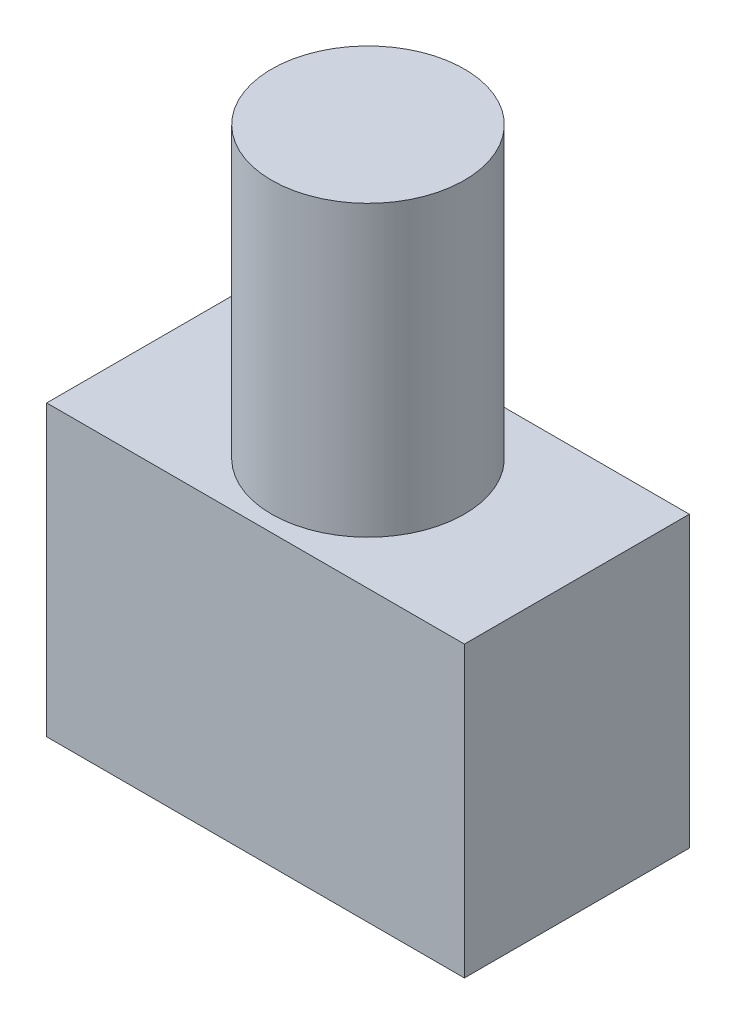
SolidWorks part; units mm, degrees
ref_plane "Front Plane" through (0, 0, 0) normal (0, 0, 1) x (1, 0, 0)
ref_plane "Top Plane" through (0, 0, 0) normal (0, 1, 0) x (1, 0, 0)
ref_plane "Right Plane" through (0, 0, 0) normal (1, 0, 0) x (0, 0, -1)
sketch "Sketch1" plane through (0, 0, 0) normal (0, 1, 0) x (1, 0, 0)
  line L1 (-6.5, 3.5) -> (6.5, 3.5)
  line L2 (-6.5, 3.5) -> (-6.5, -3.5)
  line L3 (-6.5, -3.5) -> (6.5, -3.5)
  line L4 (6.5, 3.5) -> (6.5, -3.5)
  line L5 (-6.5, 3.5) -> (6.5, -3.5) construction
  line L6 (-6.5, -3.5) -> (6.5, 3.5) construction
  point P0 (0, 0)
  dimension "D1" = 7
  dimension "D2" = 13
extrude "Boss-Extrude1" add sketch "Sketch1" along normal blind 9
sketch "Sketch2" plane through (0, 9, 0) normal (0, 1, 0) x (1, 0, 0)
  circle A0 centre (0, 0) radius 3
  dimension "D1" = 6
extrude "Boss-Extrude2" add sketch "Sketch2" along normal blind 9
